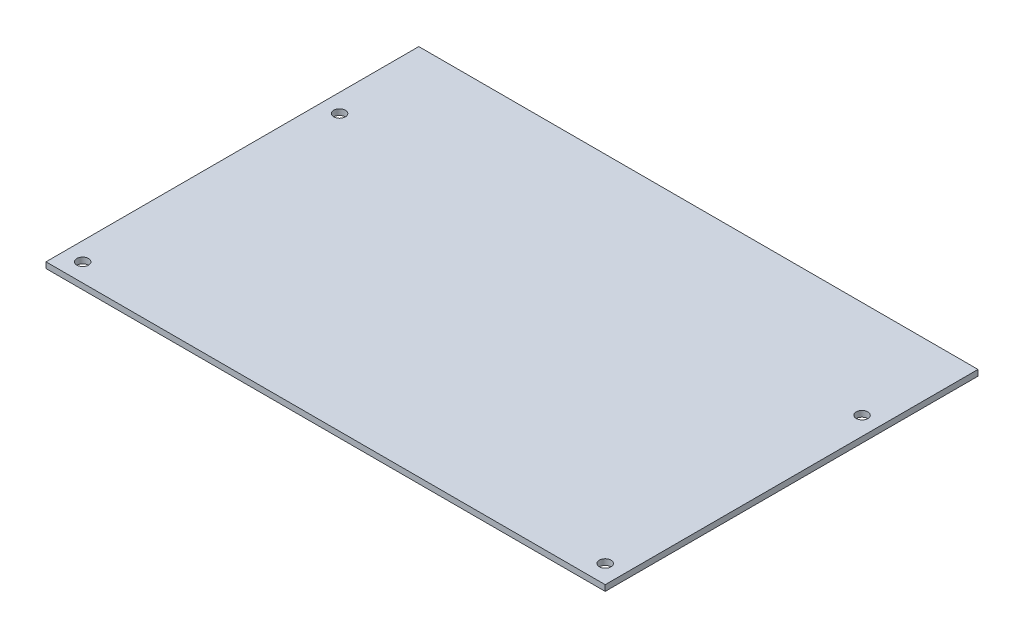
SolidWorks part; units mm, degrees
material "PBT General Purpose"
ref_plane "Ground_Plane" through (0, 0, 0) normal (0, 0, 1) x (1, 0, 0)
ref_plane "VehicleCentre_Plane" through (0, 0, 0) normal (0, 1, 0) x (1, 0, 0)
ref_plane "FrontAxle_Plane" through (0, 0, 0) normal (1, 0, 0) x (0, 0, -1)
sketch "Sketch1" plane through (0, 0, 0) normal (0, 1, 0) x (1, 0, 0)
  line L1 (76.2, -50.8) -> (-76.2, -50.8)
  line L2 (76.2, -50.8) -> (76.2, 50.8)
  line L3 (76.2, 50.8) -> (-76.2, 50.8)
  line L4 (-76.2, -50.8) -> (-76.2, 50.8)
  line L5 (76.2, -50.8) -> (-76.2, 50.8) construction
  line L6 (76.2, 50.8) -> (-76.2, -50.8) construction
  point P0 (0, 0)
  dimension "D1" = 101.6
  dimension "D2" = 152.4
extrude "Boss-Extrude1" add sketch "Sketch1" along normal blind 1.6
sketch "Sketch2" plane through (0, 0, 0) normal (0, -1, 0) x (1, 0, 0)
  line L1 (-76.2, -50.8) -> (-16.2, -50.8)
  line L2 (-76.2, -50.8) -> (-76.2, -30.8)
  line L3 (-76.2, -30.8) -> (-16.2, -30.8)
  line L4 (-16.2, -50.8) -> (-16.2, -30.8)
  line L5 (-76.2, -50.8) -> (-16.2, -30.8) construction
  line L6 (-76.2, -30.8) -> (-16.2, -50.8) construction
  line L7 (-75.2, -49.8) -> (-17.2, -49.8)
  line L8 (-75.2, -49.8) -> (-75.2, -31.8)
  line L9 (-75.2, -31.8) -> (-17.2, -31.8)
  line L10 (-17.2, -49.8) -> (-17.2, -31.8)
  line L11 (-75.2, -49.8) -> (-17.2, -31.8) construction
  line L12 (-75.2, -31.8) -> (-17.2, -49.8) construction
  point P4 (-46.2, -40.8)
  point P10 (-46.2, -40.8)
  point P11 (-76.2, -40.8)
  dimension "D1" = 1
  dimension "D2" = 1
  dimension "D3" = 1
  dimension "D4" = 20
  dimension "D5" = 1
  dimension "D6" = 60
split line "Split Line1"
sketch "Sketch3" plane through (0, 0, 0) normal (0, -1, 0) x (1, 0, 0)
  line L0 (-76.2, -30.8) -> (-76.2, 50.8) construction
  line L1 (-76.2, 50.8) -> (76.2, 50.8) construction
  line L2 (76.2, 50.8) -> (76.2, -50.8) construction
  circle A0 centre (-71.2, 45.8) radius 1.5875
  circle A1 centre (-71.2, -24.2) radius 1.5875
  circle A2 centre (71.2, -24.2) radius 1.5875
  circle A3 centre (71.2, 45.8) radius 1.5875
  dimension "D1" = 3.175
  dimension "D2" = 5
  dimension "D3" = 5
  dimension "D4" = 70
  dimension "D5" = 5
extrude "Cut-Extrude1" cut sketch "Sketch3" against normal through all
equation "\"D5@Sketch3\"=\"D2@Sketch3\""
equation "\"D2@Sketch1\"=6*25.4"
